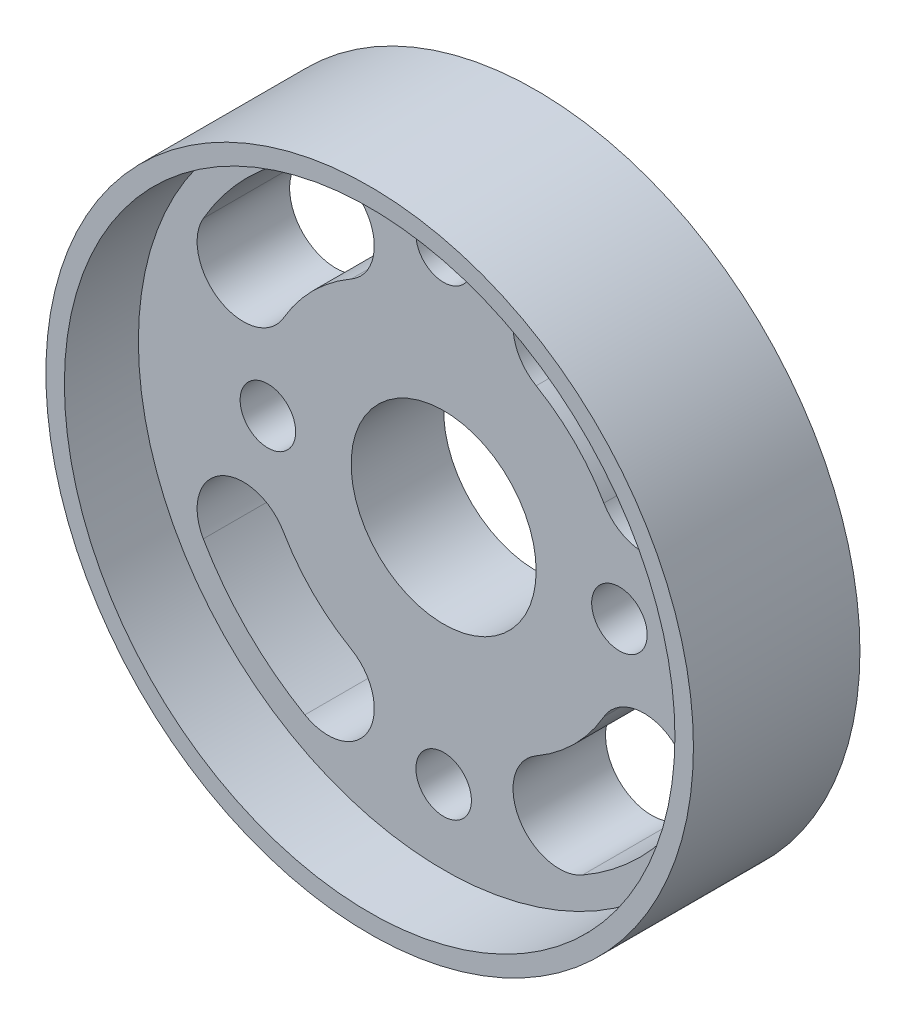
SolidWorks part; units mm, degrees
ref_plane "Front Plane" through (0, 0, 0) normal (0, 0, 1) x (1, 0, 0)
ref_plane "Top Plane" through (0, 0, 0) normal (0, 1, 0) x (1, 0, 0)
ref_plane "Right Plane" through (0, 0, 0) normal (1, 0, 0) x (0, 0, -1)
sketch "Sketch1" plane through (0, 0, 0) normal (0, 0, 1) x (1, 0, 0)
  line L0 (0, 0) -> (34.1095, 0) construction
  line L1 (0, 29.6086) -> (0, -21.1098) construction
  line L2 (0, -29.6086) -> (0, 21.1098) construction
  circle A0 centre (0, 0) radius 17.5
  circle A1 centre (0, 0) radius 12.5 construction
  circle A2 centre (0, 12.5) radius 1.5
  circle A3 centre (12.5, 0) radius 1.5 construction
  circle A4 centre (0, -12.5) radius 1.5
  circle A5 centre (-12.5, 0) radius 1.5 construction
  arc A6 (-8.6603, -5) -> (-5, -8.6603) centre (0, 0) ccw
  arc A7 (-12.9904, -7.5) -> (-7.5, -12.9904) centre (0, 0) ccw
  arc A8 (-5, 8.6603) -> (-7.5, 12.9904) centre (-6.25, 10.8253) ccw
  arc A9 (-12.9904, 7.5) -> (-8.6603, 5) centre (-10.8253, 6.25) ccw
  arc A10 (-12.9904, -7.5) -> (-8.6603, -5) centre (-10.8253, -6.25) cw
  arc A11 (-5, -8.6603) -> (-7.5, -12.9904) centre (-6.25, -10.8253) cw
  arc A12 (5, -8.6603) -> (7.5, -12.9904) centre (6.25, -10.8253) ccw
  arc A13 (12.9904, -7.5) -> (8.6603, -5) centre (10.8253, -6.25) ccw
  arc A14 (12.9904, 7.5) -> (8.6603, 5) centre (10.8253, 6.25) cw
  arc A15 (5, 8.6603) -> (7.5, 12.9904) centre (6.25, 10.8253) cw
  arc A16 (-7.5, 12.9904) -> (-12.9904, 7.5) centre (0, 0) ccw
  arc A17 (-5, 8.6603) -> (-8.6603, 5) centre (0, 0) ccw
  arc A18 (12.9904, 7.5) -> (7.5, 12.9904) centre (0, 0) ccw
  arc A19 (8.6603, 5) -> (5, 8.6603) centre (0, 0) ccw
  arc A20 (7.5, -12.9904) -> (12.9904, -7.5) centre (0, 0) ccw
  arc A21 (5, -8.6603) -> (8.6603, -5) centre (0, 0) ccw
  circle A22 centre (0, 0) radius 5
  circle A23 centre (0, 0) radius 9.5 construction
  circle A24 centre (9.5, 0) radius 1.5
  circle A25 centre (-9.5, 0) radius 1.5
  point P15 (0, 0)
  dimension "D1" = 35
  dimension "D2" = 25
  dimension "D3" = 3
  dimension "D5" = 90
  dimension "D7" = 30
  dimension "D8" = 20
  dimension "D9" = 30
  dimension "D11" = 30
  dimension "D13" = 10
  dimension "D14" = 19
  dimension "D6" = 90
  dimension "D10" = 30
  dimension "D12" = 30
  dimension "D4" = 4
extrude "Boss-Extrude1" add sketch "Sketch1" along normal blind 5
sketch "Sketch2" plane through (0, 0, 5) normal (0, 0, 1) x (1, 0, 0)
  circle A0 centre (0, 0) radius 17.5
  dimension "D1" = 35
extrude "Extrude-Thin1" add sketch "Sketch2" along normal blind 4 thin thin type one direction reverse wall 1
